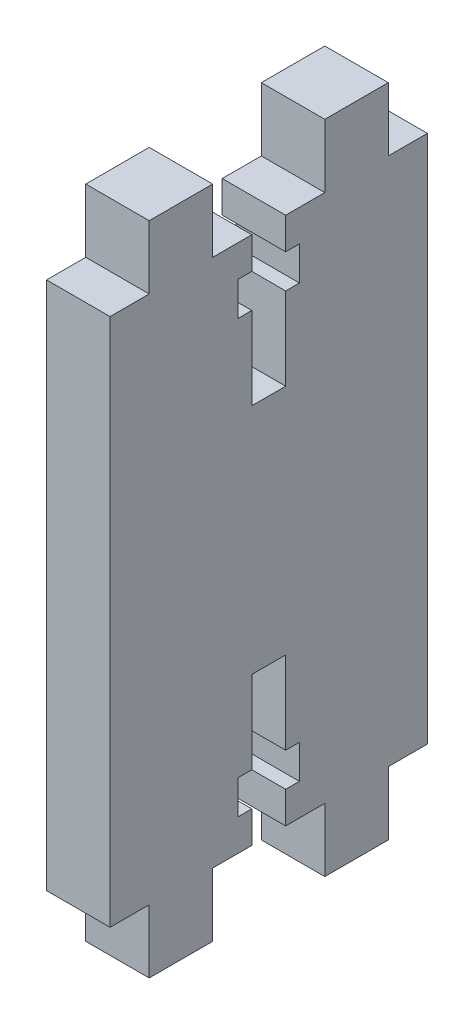
SolidWorks part; units mm, degrees
material "Oak"
ref_plane "Front Plane" through (0, 0, 0) normal (0, 0, 1) x (1, 0, 0)
ref_plane "Top Plane" through (0, 0, 0) normal (0, 1, 0) x (1, 0, 0)
ref_plane "Right Plane" through (0, 0, 0) normal (1, 0, 0) x (0, 0, -1)
sketch "Sketch1" plane through (0, 0, 0) normal (1, 0, 0) x (0, 0, -1)
  line L0 (-15, -25) -> (-15, 25)
  line L1 (-15, 25) -> (-11.3, 25)
  line L2 (-1.6, 25) -> (-1.6, 22)
  line L3 (-1.6, 22) -> (-2.9, 22)
  line L4 (-2.9, 22) -> (-2.9, 18.8)
  line L5 (-2.9, 18.8) -> (-1.6, 18.8)
  line L6 (-1.6, 18.8) -> (-1.6, 11)
  line L7 (-1.6, 11) -> (1.6, 11)
  line L8 (1.6, 11) -> (1.6, 18.8)
  line L9 (1.6, 18.8) -> (2.9, 18.8)
  line L10 (2.9, 18.8) -> (2.9, 22)
  line L11 (2.9, 22) -> (1.6, 22)
  line L12 (1.6, 22) -> (1.6, 25)
  line L13 (1.6, 25) -> (5.3, 25)
  line L14 (15, 25) -> (15, -25)
  line L15 (-5.3, 25) -> (-1.6, 25)
  line L17 (-11.3, 25) -> (-11.3, 31)
  line L18 (-11.3, 31) -> (-5.3, 31)
  line L19 (-5.3, 25) -> (-5.3, 31)
  line L20 (0, 55) -> (0, -55) construction
  line L21 (5.3, 25) -> (5.3, 31)
  line L22 (11.3, 31) -> (5.3, 31)
  line L23 (11.3, 25) -> (11.3, 31)
  line L24 (11.3, 25) -> (15, 25)
  line L25 (55, 0) -> (-55, 0) construction
  line L26 (11.3, -25) -> (15, -25)
  line L27 (11.3, -25) -> (11.3, -31)
  line L28 (11.3, -31) -> (5.3, -31)
  line L29 (5.3, -25) -> (5.3, -31)
  line L30 (-5.3, -25) -> (-5.3, -31)
  line L31 (-11.3, -31) -> (-5.3, -31)
  line L32 (-11.3, -25) -> (-11.3, -31)
  line L33 (-5.3, -25) -> (-1.6, -25)
  line L34 (1.6, -25) -> (5.3, -25)
  line L35 (1.6, -22) -> (1.6, -25)
  line L36 (2.9, -22) -> (1.6, -22)
  line L37 (2.9, -18.8) -> (2.9, -22)
  line L38 (1.6, -18.8) -> (2.9, -18.8)
  line L39 (1.6, -11) -> (1.6, -18.8)
  line L40 (-1.6, -11) -> (1.6, -11)
  line L41 (-1.6, -18.8) -> (-1.6, -11)
  line L42 (-2.9, -18.8) -> (-1.6, -18.8)
  line L43 (-2.9, -22) -> (-2.9, -18.8)
  line L44 (-1.6, -22) -> (-2.9, -22)
  line L45 (-1.6, -25) -> (-1.6, -22)
  line L46 (-15, -25) -> (-11.3, -25)
  point P44 (15, 0)
  point P56 (-15, 0)
  dimension "D3" = 3.2
  dimension "D4" = 25
  dimension "D5" = 3.2
  dimension "D6" = 5.8
  dimension "D7" = 3
  dimension "D8" = 20
  dimension "D9" = 6
  dimension "D10" = 6
  dimension "D2" = 30
extrude "Boss-Extrude1" add sketch "Sketch1" along normal blind 6
